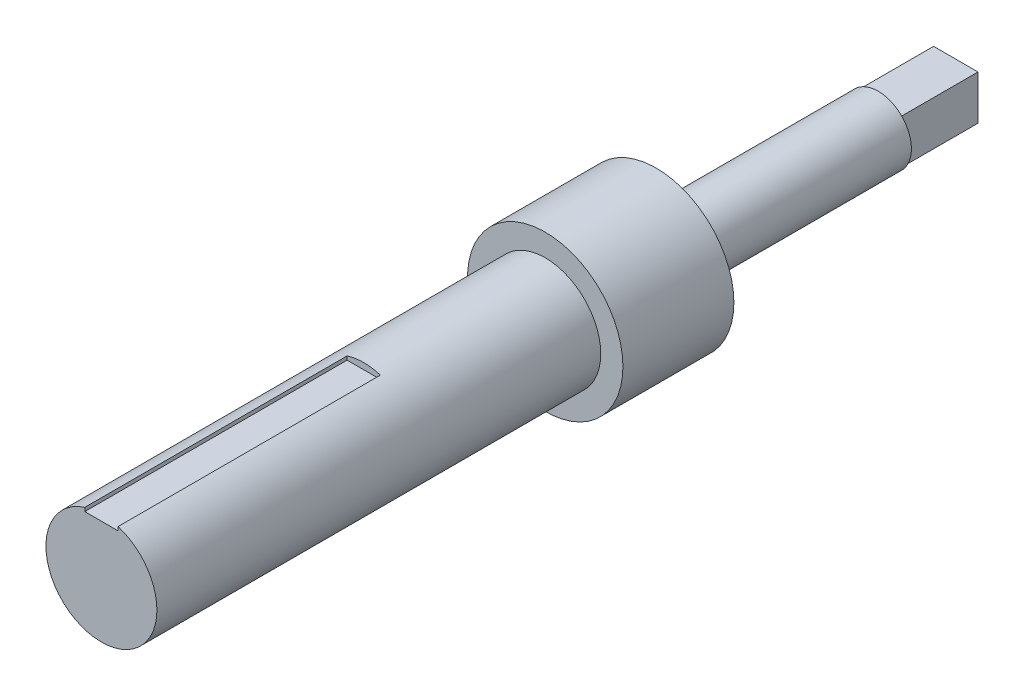
SolidWorks part; units mm, degrees
ref_plane "前视基准面" through (0, 0, 0) normal (0, 0, 1) x (1, 0, 0)
ref_plane "上视基准面" through (0, 0, 0) normal (0, 1, 0) x (1, 0, 0)
ref_plane "右视基准面" through (0, 0, 0) normal (1, 0, 0) x (0, 0, -1)
sketch "草图1" plane through (0, 0, 0) normal (0, 0, 1) x (1, 0, 0)
  circle A0 centre (0, 0) radius 3.5
  dimension "D1" = 7
extrude "拉伸1" add sketch "草图1" along normal blind 25
sketch "草图2" plane through (0, 0, 0) normal (0, 0, -1) x (-1, 0, 0)
  circle A0 centre (0, 0) radius 1.5
  dimension "D1" = 3
extrude "拉伸2" add sketch "草图2" along normal blind 10
sketch "草图3" plane through (0, 0, -10) normal (0, 0, -1) x (-1, 0, 0)
  line L0 (0, 4.1868) -> (0, -4.1296) construction
  line L1 (-1, 1) -> (1, 1)
  line L2 (-1, 1) -> (-1, -1)
  line L3 (-1, -1) -> (1, -1)
  line L4 (1, 1) -> (1, -1)
  line L5 (-4.3115, 0) -> (5.3976, 0) construction
  dimension "D1" = 2
extrude "拉伸3" add sketch "草图3" along normal blind 3.5
sketch "草图4" plane through (0, 0, 25) normal (0, 0, 1) x (1, 0, 0)
  circle A0 centre (0, 0) radius 2.5
  dimension "D1" = 5
extrude "切除-拉伸1" cut sketch "草图4" against normal blind 20 flip side to cut
sketch "草图5" plane through (0, 0, 25) normal (0, 0, 1) x (1, 0, 0)
  line L0 (0, 3.7186) -> (0, -1.2755) construction
  line L1 (-0.75, 2.7647) -> (0.75, 2.7647)
  line L2 (-0.75, 2.7647) -> (-0.75, 2.2176)
  line L3 (-0.75, 2.2176) -> (0.75, 2.2176)
  line L4 (0.75, 2.7647) -> (0.75, 2.2176)
  dimension "D1" = 1.5
extrude "切除-拉伸2" cut sketch "草图5" against normal blind 11.8201
